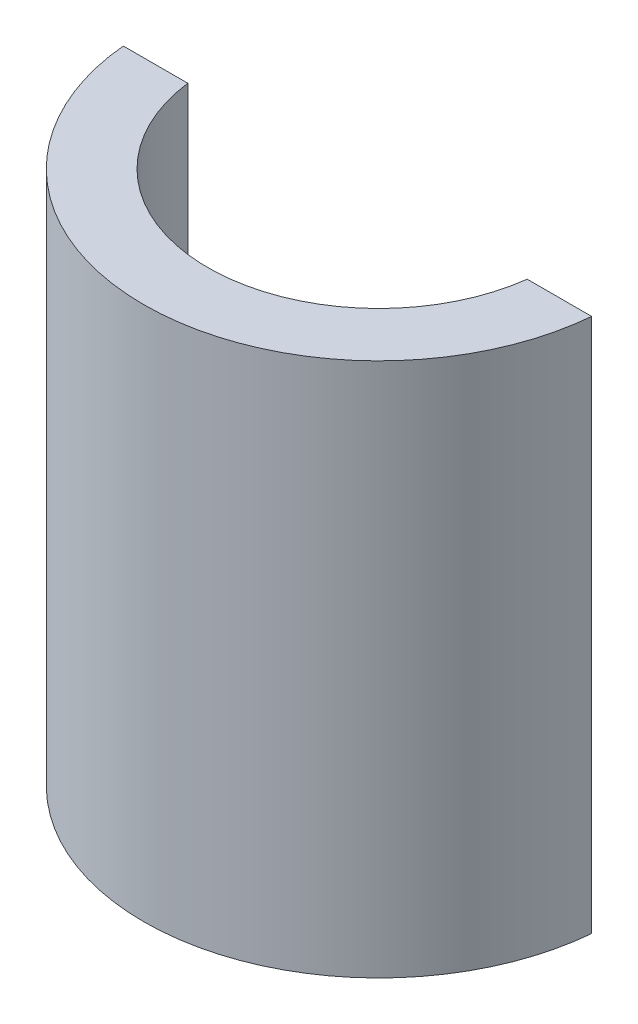
SolidWorks part; units mm, degrees
material "ABS"
ref_plane "Front Plane" through (0, 0, 0) normal (0, 0, 1) x (1, 0, 0)
ref_plane "Top Plane" through (0, 0, 0) normal (0, 1, 0) x (1, 0, 0)
ref_plane "Right Plane" through (0, 0, 0) normal (1, 0, 0) x (0, 0, -1)
sketch "Sketch1" plane through (0, 0, 0) normal (0, 1, 0) x (1, 0, 0)
  line L0 (-10.9545, -1) -> (-7.9373, -1)
  line L1 (7.9373, -1) -> (10.9545, -1)
  arc A0 (-10.9545, -1) -> (10.9545, -1) centre (0, 0) ccw
  arc A1 (-7.9373, -1) -> (7.9373, -1) centre (0, 0) ccw
  dimension "D1" = 16
  dimension "D2" = 22
  dimension "D3" = 1
extrude "Boss-Extrude1" add sketch "Sketch1" along normal blind 25
